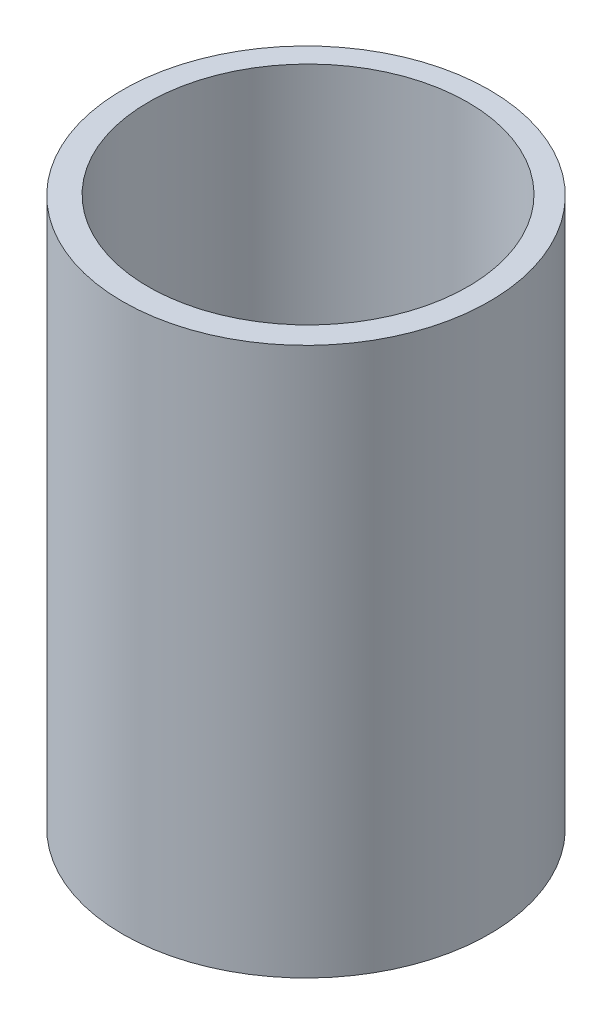
SolidWorks part; units mm, degrees
ref_plane "Front Plane" through (0, 0, 0) normal (0, 0, 1) x (1, 0, 0)
ref_plane "Top Plane" through (0, 0, 0) normal (0, 1, 0) x (1, 0, 0)
ref_plane "Right Plane" through (0, 0, 0) normal (1, 0, 0) x (0, 0, -1)
sketch "Sketch1" plane through (0, 0, 0) normal (0, 1, 0) x (1, 0, 0)
  circle A0 centre (0, 0) radius 51
  circle A1 centre (0, 0.567) radius 44.45
  dimension "D1" = 102
  dimension "D2" = 88.9
extrude "Boss-Extrude1" add sketch "Sketch1" along normal blind 152.4
